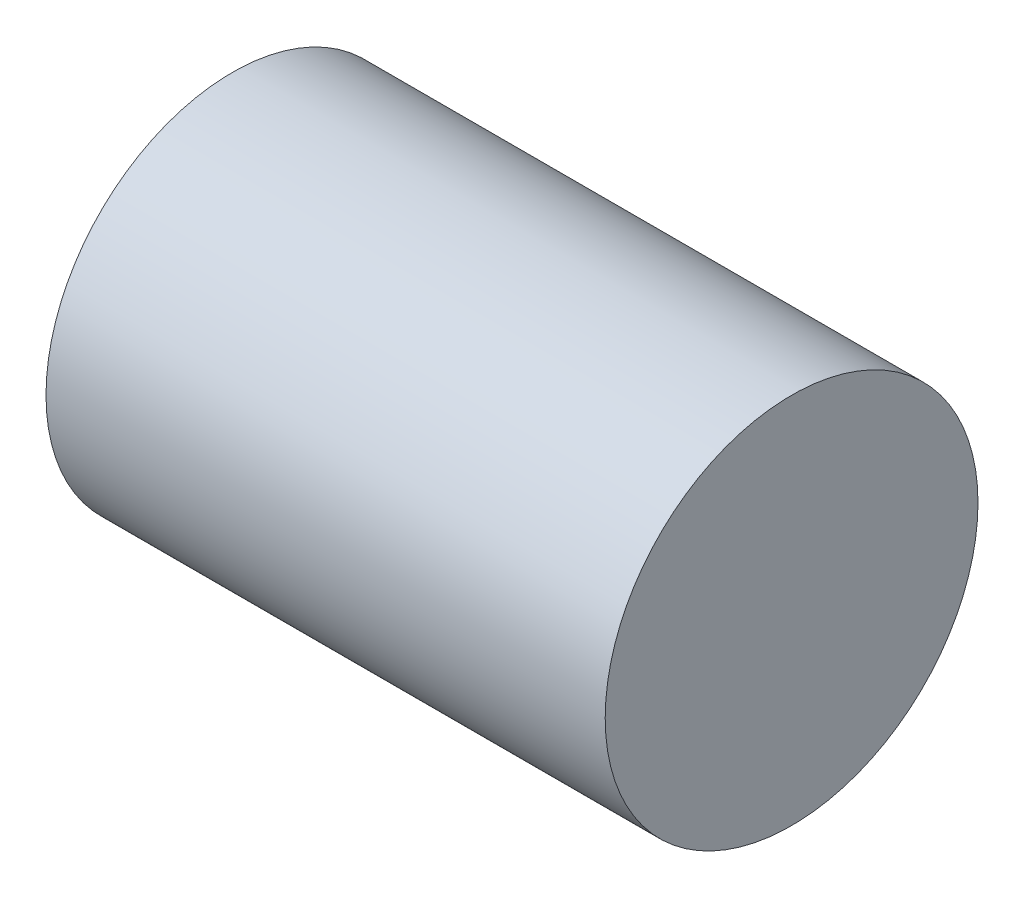
SolidWorks part; units mm, degrees
ref_plane "Front Plane" through (0, 0, 0) normal (0, 0, 1) x (1, 0, 0)
ref_plane "Top Plane" through (0, 0, 0) normal (0, 1, 0) x (1, 0, 0)
ref_plane "Right Plane" through (0, 0, 0) normal (1, 0, 0) x (0, 0, -1)
sketch "Sketch2" plane through (0, 0, 0) normal (1, 0, 0) x (0, 0, -1)
  circle A0 centre (0, 0) radius 10
  dimension "D1" = 20
extrude "Boss-Extrude1" add sketch "Sketch2" against normal blind 30
